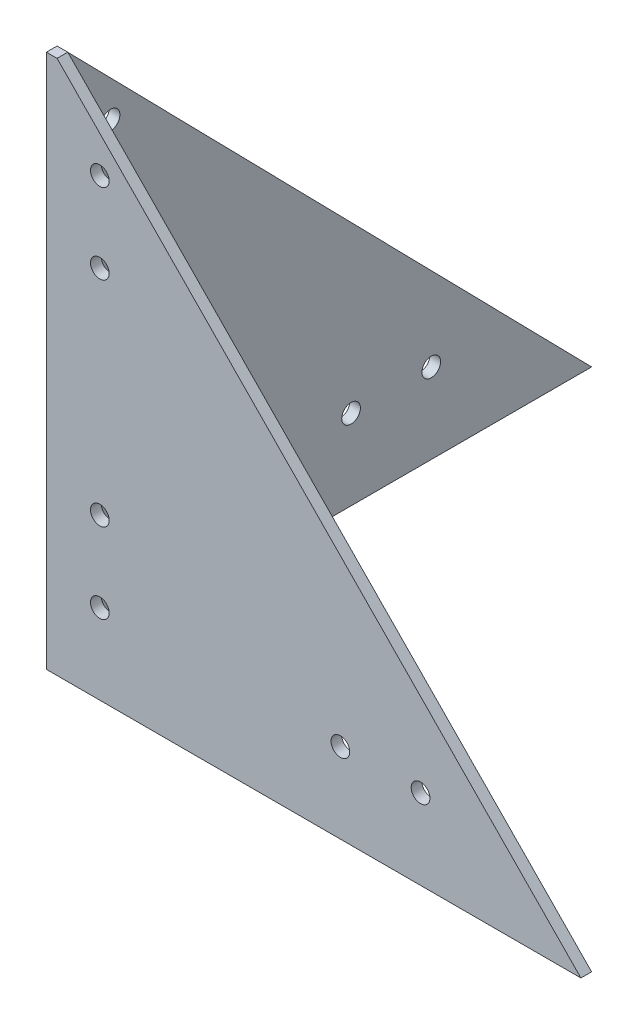
SolidWorks part; units mm, degrees
ref_plane "Plano frontal" through (0, 0, 0) normal (0, 0, 1) x (1, 0, 0)
ref_plane "Plano superior" through (0, 0, 0) normal (0, 1, 0) x (1, 0, 0)
ref_plane "Plano direito" through (0, 0, 0) normal (1, 0, 0) x (0, 0, -1)
sketch "Esboço1" plane through (0, 0, 0) normal (0, 1, 0) x (1, 0, 0)
  line L1 (0, 0) -> (2, 0)
  line L2 (0, 0) -> (0, 2)
  line L3 (0, 2) -> (2, 2)
  line L4 (2, 0) -> (2, 2)
  dimension "D1" = 2
  dimension "D2" = 2
extrude "Ressalto-extrusão1" add sketch "Esboço1" along normal blind 100
sketch "Esboço2" plane through (0, 0, 0) normal (0, 0, 1) x (1, 0, 0)
  line L0 (2, 0) -> (100, 0)
  line L1 (100, 0) -> (2, 100)
  line L2 (2, 100) -> (2, 0)
  dimension "D1" = 98
extrude "Ressalto-extrusão2" add sketch "Esboço2" against normal blind 2
sketch "Esboço3" plane through (0, 0, 0) normal (-1, 0, 0) x (0, 0, 1)
  line L0 (-2, 0) -> (-2, 100)
  line L1 (-2, 100) -> (-100, 0)
  line L2 (-100, 0) -> (-2, 0)
  dimension "D1" = 98
extrude "Ressalto-extrusão3" add sketch "Esboço3" against normal blind 2
sketch "Esboço4" plane through (0, 0, 0) normal (-1, 0, 0) x (0, 0, 1)
  line L0 (0, 100) -> (0, 0) construction
  line L2 (-100, 0) -> (0, 0) construction
  line L3 (-2, 100) -> (0, 100) construction
  circle A0 centre (-10, 15) radius 1.75
  circle A1 centre (-10, 30) radius 1.75
  circle A2 centre (-10, 85) radius 1.75
  circle A3 centre (-10, 70) radius 1.75
  circle A4 centre (-55, 15) radius 1.75
  circle A5 centre (-70, 15) radius 1.75
  point P16 (-9.6642, 0)
  dimension "D1" = 3.5
  dimension "D2" = 3.5
  dimension "D3" = 3.5
  dimension "D4" = 3.5
  dimension "D17" = 3.5
  dimension "D18" = 3.5
  dimension "D5" = 10
  dimension "D6" = 10
  dimension "D7" = 10
  dimension "D8" = 10
  dimension "D9" = 15
  dimension "D10" = 15
  dimension "D11" = 15
  dimension "D12" = 15
  dimension "D13" = 15
  dimension "D14" = 30
  dimension "D15" = 15
  dimension "D16" = 15
sketch "Esboço5" plane through (0, 0, 0) normal (0, 0, 1) x (1, 0, 0)
  line L4 (0, 0) -> (100, 0) construction
  line L5 (0, 100) -> (0, 0) construction
  line L6 (0, 100) -> (2, 100) construction
  circle A0 centre (10, 15) radius 1.75
  circle A1 centre (10, 30) radius 1.75
  circle A2 centre (10, 85) radius 1.75
  circle A3 centre (10, 70) radius 1.75
  circle A4 centre (70, 15) radius 1.75
  circle A5 centre (55, 15) radius 1.75
  point P16 (57.4689, -30.8683)
  dimension "D1" = 3.5
  dimension "D2" = 3.5
  dimension "D3" = 3.5
  dimension "D4" = 3.5
  dimension "D17" = 3.5
  dimension "D18" = 3.5
  dimension "D5" = 15
  dimension "D6" = 10
  dimension "D7" = 15
  dimension "D8" = 10
  dimension "D9" = 30
  dimension "D10" = 15
  dimension "D11" = 15
  dimension "D12" = 15
  dimension "D13" = 0
  dimension "D15" = 15
extrude "Corte-extrusão1" cut sketch "Esboço4" against normal blind 2
extrude "Corte-extrusão2" cut sketch "Esboço5" against normal blind 2
